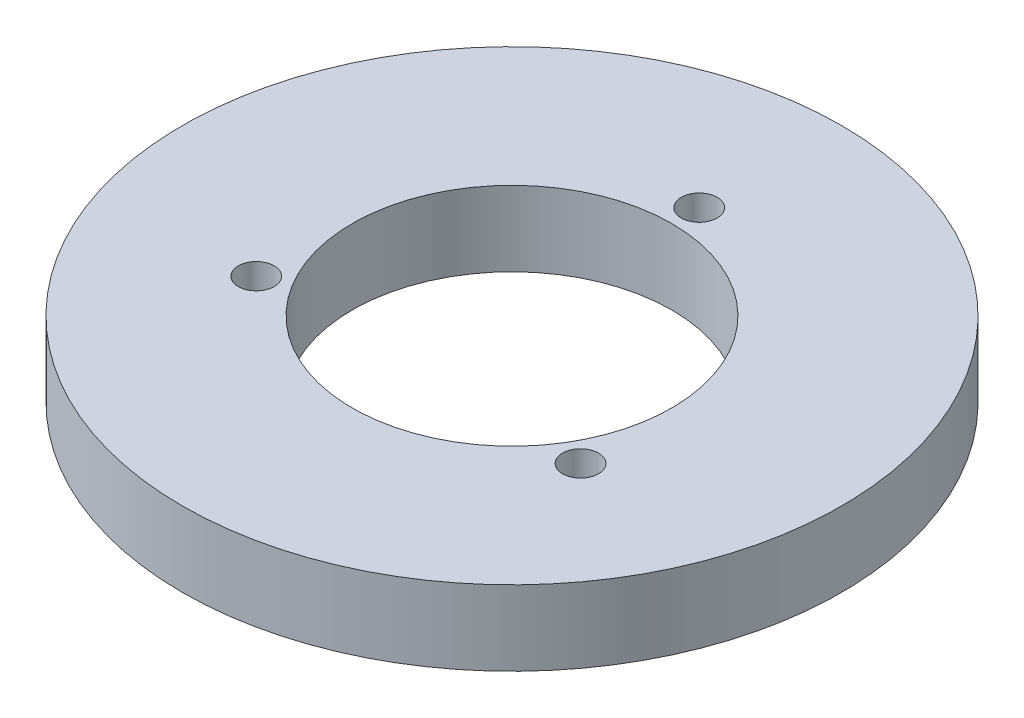
SolidWorks part; units mm, degrees
material "AISI 304"
ref_plane "Front Plane" through (0, 0, 0) normal (0, 0, 1) x (1, 0, 0)
ref_plane "Top Plane" through (0, 0, 0) normal (0, 1, 0) x (1, 0, 0)
ref_plane "Right Plane" through (0, 0, 0) normal (1, 0, 0) x (0, 0, -1)
sketch "Sketch1" plane through (0, 0, 0) normal (0, 1, 0) x (1, 0, 0)
  circle A0 centre (0, 0) radius 41.91
  circle A1 centre (0, 0) radius 20.32
  dimension "D1" = 83.82
  dimension "D2" = 40.64
extrude "Boss-Extrude1" add sketch "Sketch1" along normal blind 9.525
sketch "Sketch2" plane through (0, 9.525, 0) normal (0, 1, 0) x (1, 0, 0)
  circle A0 centre (0, 23.8125) radius 2.286
  circle A1 centre (20.6222, -11.9062) radius 2.286
  circle A2 centre (-20.6222, -11.9063) radius 2.286
  point P9 (0, 0)
  dimension "D1" = 4.572
  dimension "D2" = 23.8125
extrude "Cut-Extrude1" cut sketch "Sketch2" against normal through all
